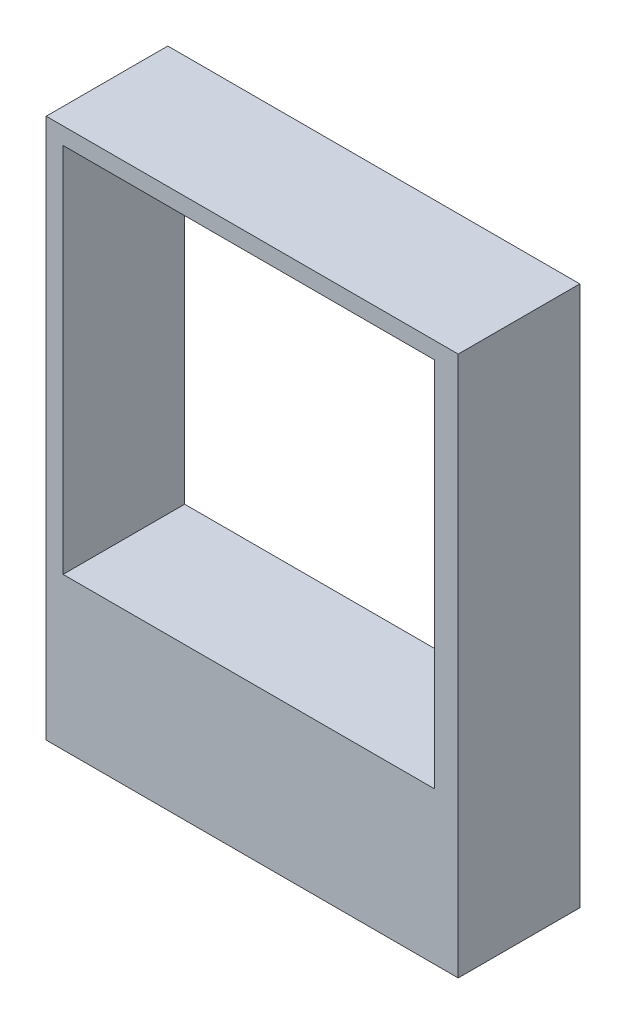
SolidWorks part; units mm, degrees
ref_plane "Plan de face" through (0, 0, 0) normal (0, 0, 1) x (1, 0, 0)
ref_plane "Plan de dessus" through (0, 0, 0) normal (0, 1, 0) x (1, 0, 0)
ref_plane "Plan de droite" through (0, 0, 0) normal (1, 0, 0) x (0, 0, -1)
sketch "Esquisse1" plane through (0, 0, 0) normal (0, 0, 1) x (1, 0, 0)
  line L1 (3.1229, 2.1784) -> (125.1229, 2.1784)
  line L2 (3.1229, 2.1784) -> (3.1229, 162.1784)
  line L3 (3.1229, 162.1784) -> (125.1229, 162.1784)
  line L4 (125.1229, 2.1784) -> (125.1229, 162.1784)
  line L5 (8.1229, 157.1784) -> (118.1229, 157.1784)
  line L6 (8.1229, 157.1784) -> (8.1229, 47.1784)
  line L7 (8.1229, 47.1784) -> (118.1229, 47.1784)
  line L8 (118.1229, 157.1784) -> (118.1229, 47.1784)
  dimension "D1" = 160
  dimension "D2" = 122
  dimension "D3" = 110
  dimension "D4" = 5
  dimension "D5" = 5
  dimension "D6" = 110
extrude "Boss.-Extru.1" add sketch "Esquisse1" along normal blind 36
